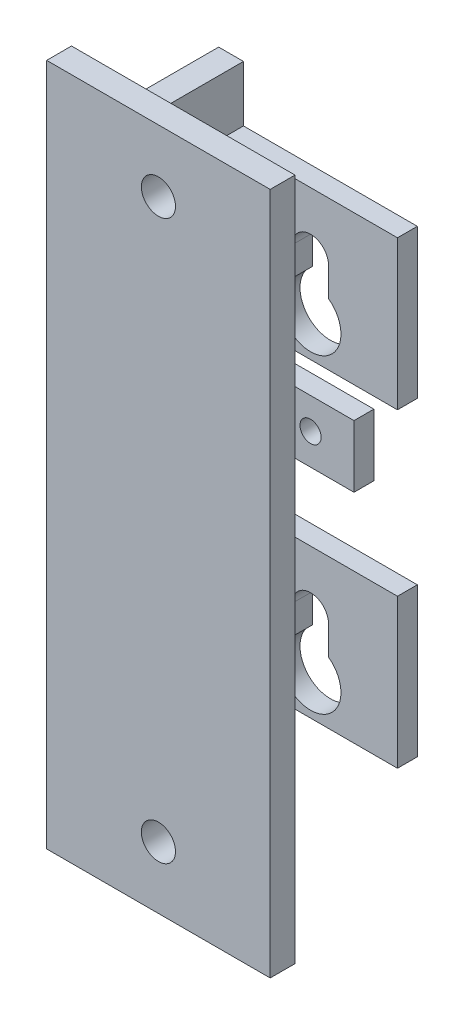
SolidWorks part; units mm, degrees
material "AISI 1020"
ref_plane "Front Plane" through (0, 0, 0) normal (0, 0, 1) x (1, 0, 0)
ref_plane "Top Plane" through (0, 0, 0) normal (0, 1, 0) x (1, 0, 0)
ref_plane "Right Plane" through (0, 0, 0) normal (1, 0, 0) x (0, 0, -1)
sketch "Sketch1" plane through (0, 0, 0) normal (0, 0, 1) x (1, 0, 0)
  line L0 (-38, -55) -> (-2, -55)
  line L1 (-2, -55) -> (-2, 55)
  line L2 (-2, 55) -> (-38, 55)
  line L3 (-38, 55) -> (-38, -55)
extrude "Wall_mounting_plate_4mm" add sketch "Sketch1" along normal blind 4 from offset 68
sketch "Sketch2" plane through (0, 0, 0) normal (0, 0, 1) x (1, 0, 0)
  line L0 (-38, -43) -> (-34, -43)
  line L1 (-34, -43) -> (-34, 43)
  line L2 (-34, 43) -> (-38, 43)
  line L3 (-38, 43) -> (-38, -43)
extrude "Side_offset_web" add sketch "Sketch2" along normal blind 24 from offset 44.3
sketch "Sketch3" plane through (0, 0, 0) normal (0, 0, 1) x (1, 0, 0)
  line L0 (-38, -40) -> (-6, -40)
  line L1 (-6, -40) -> (-6, -16)
  line L2 (-6, -16) -> (-38, -16)
  line L3 (-38, -16) -> (-38, -40)
  line L4 (-38, 10) -> (-6, 10)
  line L5 (-6, 10) -> (-6, 34)
  line L6 (-6, 34) -> (-38, 34)
  line L7 (-38, 34) -> (-38, 10)
extrude "Two_peg_receiver_tabs" add sketch "Sketch3" along normal blind 3.2 from offset 44.3
sketch "Sketch4" plane through (0, 0, 0) normal (0, 0, 1) x (1, 0, 0)
  circle A0 centre (-20, -34) radius 4.9
  circle A1 centre (-20, 16) radius 4.9
extrude "Peg_head_entry_D9p8" cut sketch "Sketch4" along normal blind 9 from offset 43
sketch "Sketch5" plane through (0, 0, 0) normal (0, 0, 1) x (1, 0, 0)
  line L0 (-22.9, -34) -> (-17.1, -34)
  line L1 (-17.1, -34) -> (-17.1, -25.4)
  line L2 (-17.1, -25.4) -> (-22.9, -25.4)
  line L3 (-22.9, -25.4) -> (-22.9, -34)
  line L4 (-22.9, 16) -> (-17.1, 16)
  line L5 (-17.1, 16) -> (-17.1, 24.6)
  line L6 (-17.1, 24.6) -> (-22.9, 24.6)
  line L7 (-22.9, 24.6) -> (-22.9, 16)
extrude "Drop_in_peg_slots_W5p8" cut sketch "Sketch5" along normal blind 9 from offset 43
sketch "Sketch6" plane through (0, 0, 0) normal (0, 0, 1) x (1, 0, 0)
  circle A0 centre (-20, -25.4) radius 2.9
  circle A1 centre (-20, 24.6) radius 2.9
extrude "Rounded_load_seats" cut sketch "Sketch6" along normal blind 9 from offset 43
sketch "Sketch7" plane through (0, 0, 0) normal (0, 0, 1) x (1, 0, 0)
  circle A0 centre (-20, -45) radius 2.75
  circle A1 centre (-20, 45) radius 2.75
extrude "Wall_screw_clearance_D5p5" cut sketch "Sketch7" along normal blind 7 from offset 67
sketch "Sketch8" plane through (0, 0, 0) normal (0, 0, 1) x (1, 0, 0)
  line L0 (-38, -5) -> (-13, -5)
  line L1 (-13, -5) -> (-13, 5)
  line L2 (-13, 5) -> (-38, 5)
  line L3 (-38, 5) -> (-38, -5)
extrude "Anti_lift_lock_tab" add sketch "Sketch8" along normal blind 3.2 from offset 44.3
sketch "Sketch9" plane through (0, 0, 0) normal (0, 0, 1) x (1, 0, 0)
  circle A0 centre (-20, 0) radius 1.7
extrude "Anti_lift_screw_clearance_D3p4" cut sketch "Sketch9" along normal blind 7 from offset 43
